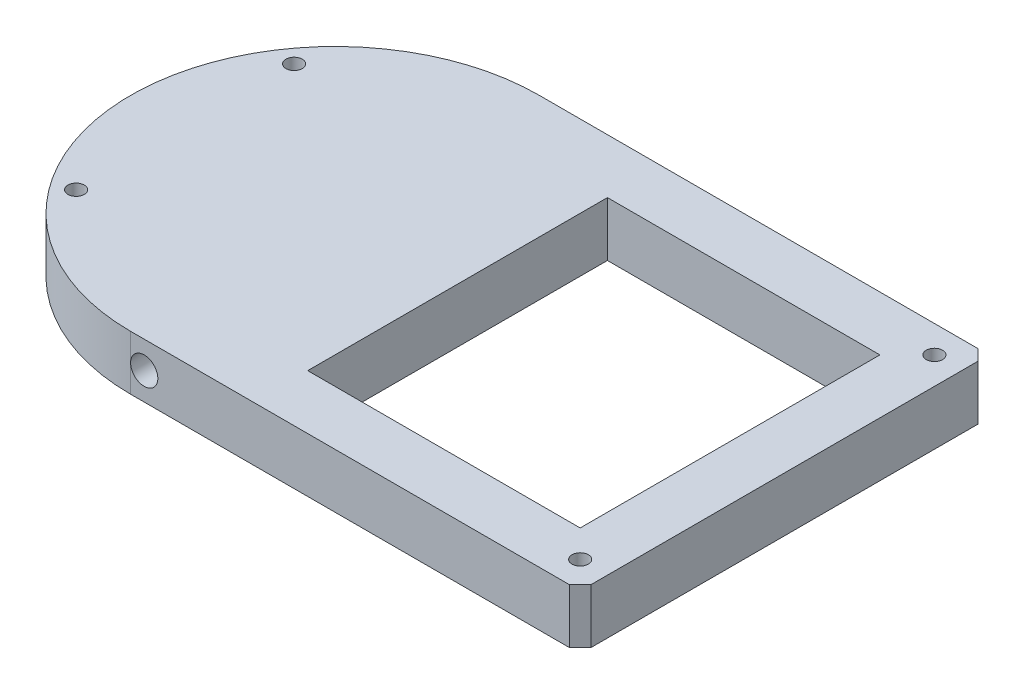
SolidWorks part; units mm, degrees
ref_plane "前视基准面" through (0, 0, 0) normal (0, 0, 1) x (1, 0, 0)
ref_plane "上视基准面" through (0, 0, 0) normal (0, 1, 0) x (1, 0, 0)
ref_plane "右视基准面" through (0, 0, 0) normal (1, 0, 0) x (0, 0, -1)
sketch "草图1" plane through (0, 0, 0) normal (0, 1, 0) x (1, 0, 0)
  line L0 (0, 37.5) -> (82.5, 37.5)
  line L1 (82.5, 37.5) -> (82.5, -37.5)
  line L2 (82.5, -37.5) -> (0, -37.5)
  arc A0 (0, 37.5) -> (0, -37.5) centre (0, 0) ccw
  point P1 (-37.5, 0)
  dimension "D1" = 75
  dimension "D2" = 120
extrude "凸台-拉伸1" add sketch "草图1" along normal blind 10
sketch "草图2" plane through (0, 0, 37.5) normal (0, 0, 1) x (1, 0, 0)
  line L0 (82.5, 5) -> (0, 5) construction
  line L1 (82.5, 10) -> (82.5, 0) construction
  line L2 (0, 10) -> (0, 0) construction
  circle A0 centre (2.5, 5) radius 2.5
  point P8 (0, 0)
  dimension "D1" = 5
extrude "切除-拉伸1" cut sketch "草图2" against normal through all
sketch "草图3" plane through (0, 10, 0) normal (0, 1, 0) x (1, 0, 0)
  line L0 (82.5, 0) -> (-37.5, 0) construction
  line L1 (82.5, -37.5) -> (82.5, 37.5) construction
  arc A0 (0, 37.5) -> (0, -37.5) centre (0, 0) ccw construction
  circle A1 centre (-27.5, 20) radius 1.5
  circle A2 centre (-27.5, -20) radius 1.5
  circle A3 centre (77.5, 32.5) radius 1.5
  circle A4 centre (77.5, -32.5) radius 1.5
  point P15 (0, 0)
  dimension "D1" = 3
  dimension "D2" = 3
  dimension "D5" = 65
  dimension "D3" = 40
  dimension "D4" = 10
  dimension "D6" = 5
extrude "切除-拉伸2" cut sketch "草图3" against normal through all
sketch "草图4" plane through (0, 10, 0) normal (0, 1, 0) x (1, 0, 0)
  line L0 (-37.5, 0) -> (82.5, 0) construction
  line L1 (82.5, -37.5) -> (82.5, 37.5) construction
  line L2 (82.5, 37.5) -> (0, 37.5) construction
  line L3 (72.5, -27.5) -> (22.5, -27.5)
  line L4 (72.5, -27.5) -> (72.5, 27.5)
  line L5 (72.5, 27.5) -> (22.5, 27.5)
  line L6 (22.5, -27.5) -> (22.5, 27.5)
  line L7 (72.5, -27.5) -> (22.5, 27.5) construction
  line L8 (72.5, 27.5) -> (22.5, -27.5) construction
  arc A0 (0, 37.5) -> (0, -37.5) centre (0, 0) ccw construction
  point P9 (47.5, 0)
  dimension "D1" = 10
  dimension "D2" = 10
  dimension "D3" = 50
extrude "切除-拉伸3" cut sketch "草图4" against normal through all
chamfer "倒角1" distance 2 angle 45 2 edges at (82.5, 5, 37.5) (82.5, 5, -37.5)
